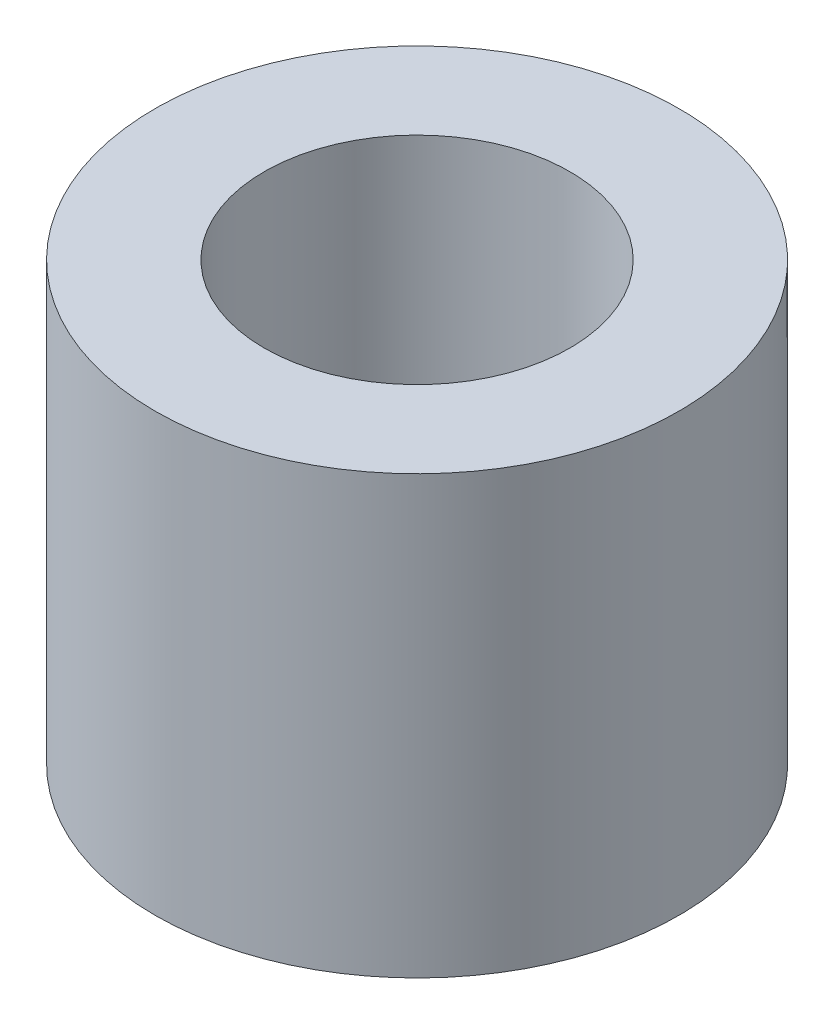
SolidWorks part; units mm, degrees
material "ABS"
ref_plane "Front" through (0, 0, 0) normal (0, 0, 1) x (1, 0, 0)
ref_plane "Top" through (0, 0, 0) normal (0, 1, 0) x (1, 0, 0)
ref_plane "Right" through (0, 0, 0) normal (1, 0, 0) x (0, 0, -1)
sketch "草图1" plane through (0, 0, 0) normal (0, 1, 0) x (1, 0, 0)
  circle A0 centre (0, 0) radius 3.6
  circle A1 centre (0, 0) radius 2.1
  dimension "垫圈内径" = 4.2
  dimension "垫圈外径" = 7.2
extrude "凸台-拉伸1" add sketch "草图1" along normal mid plane 6
other "冻结***"
